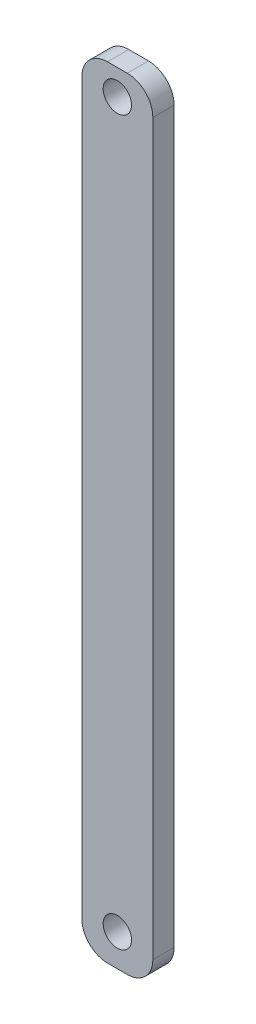
SolidWorks part; units mm, degrees
ref_plane "Front Plane" through (0, 0, 0) normal (0, 0, 1) x (1, 0, 0)
ref_plane "Top Plane" through (0, 0, 0) normal (0, 1, 0) x (1, 0, 0)
ref_plane "Right Plane" through (0, 0, 0) normal (1, 0, 0) x (0, 0, -1)
sketch "Sketch3" plane through (0, 0, 0) normal (0, 0, 1) x (1, 0, 0)
  line L0 (12.7, 0) -> (-12.7, 0)
  line L1 (-12.7, -228.6) -> (-12.7, 228.6)
  line L2 (13.97, 0) -> (-13.97, 0) construction
  line L3 (12.7, -228.6) -> (12.7, 228.6)
  point P4 (0, 0)
  point P9 (-12.7, 0)
  point P11 (12.7, 0)
sketch "Sketch5" plane through (0, 0, 0) normal (0, 0, 1) x (1, 0, 0)
  line L0 (-12.7, 228.6) -> (12.7, 228.6)
  line L1 (-12.7, -228.6) -> (12.7, -228.6)
sketch "Sketch7" plane through (0, 0, 0) normal (0, 0, 1) x (1, 0, 0)
  line L1 (37.3, -321.4) -> (-12.7, -321.4)
  line L2 (37.3, -321.4) -> (37.3, 228.6)
  line L3 (37.3, 228.6) -> (-12.7, 228.6)
  line L4 (-12.7, -321.4) -> (-12.7, 228.6)
  line L5 (37.3, -321.4) -> (-12.7, 228.6) construction
  line L6 (37.3, 228.6) -> (-12.7, -321.4) construction
extrude "Boss-Extrude1" add sketch "Sketch7" along normal mid plane 15
fillet "Fillet1" radius 18 4 edges at (37.3, -321.4, 0) (-12.7, -321.4, 0) (-12.7, 228.6, 0) (37.3, 228.6, 0)
sketch "Sketch8" plane through (0, 0, 7.5) normal (0, 0, 1) x (1, 0, 0)
  line L1 (-12.7, 210.6) -> (37.3, 210.6) construction
  circle A1 centre (12.3, 210.6) radius 10
extrude "Cut-Extrude1" cut sketch "Sketch8" against normal through all
sketch "Sketch9" plane through (0, 0, 7.5) normal (0, 0, 1) x (1, 0, 0)
  line L0 (-12.7, -298.8423) -> (37.3, -298.8423) construction
  line L1 (-12.7, 210.6) -> (-12.7, -303.4) construction
  line L2 (37.3, -303.4) -> (37.3, 210.6) construction
  circle A0 centre (12.3, -298.8423) radius 10
  point P8 (12.3, -338.2351)
  point P9 (12.3, -343.2703)
  point P10 (12.3, -298.8423)
extrude "Cut-Extrude2" cut sketch "Sketch9" against normal through all
